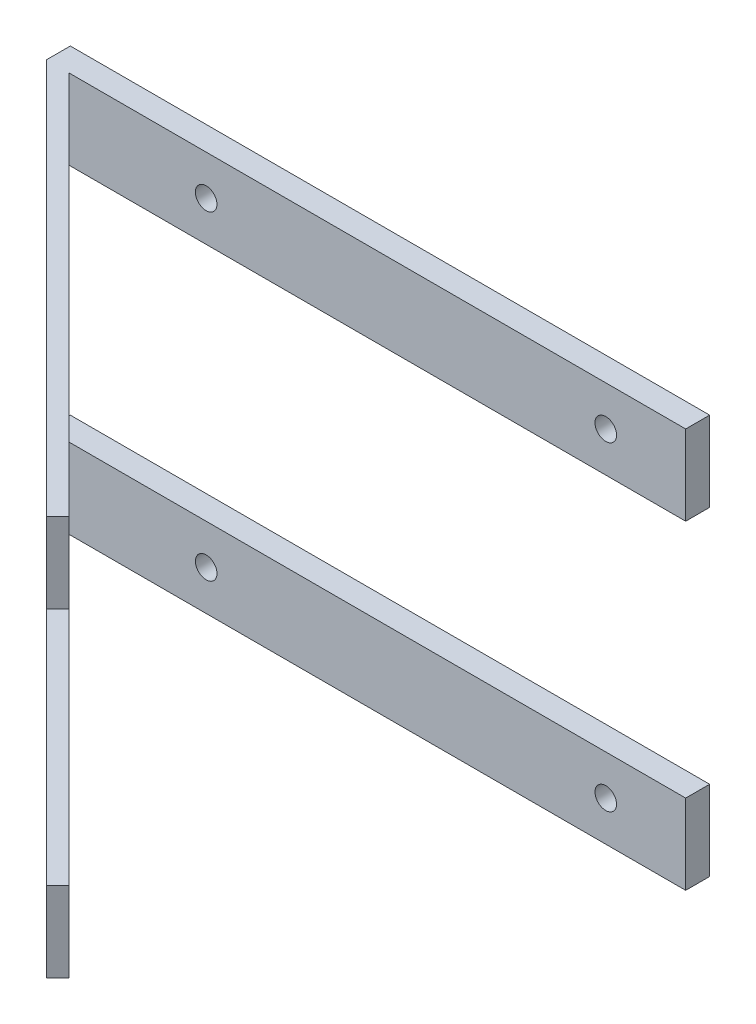
SolidWorks part; units mm, degrees
ref_plane "Alzado" through (0, 0, 0) normal (0, 0, 1) x (1, 0, 0)
ref_plane "Planta" through (0, 0, 0) normal (0, 1, 0) x (1, 0, 0)
ref_plane "Vista lateral" through (0, 0, 0) normal (1, 0, 0) x (0, 0, -1)
sketch "Croquis1" plane through (0, 0, 0) normal (0, 0, 1) x (1, 0, 0)
  line L0 (-50, 25) -> (40, 25) construction
  line L1 (-40, 10) -> (40, 10)
  line L2 (-40, 10) -> (-40, 0)
  line L3 (-40, 0) -> (40, 0)
  line L4 (40, 10) -> (40, 0)
  line L5 (40, 40) -> (40, 50)
  line L6 (-40, 50) -> (40, 50)
  line L7 (-40, 40) -> (-40, 50)
  line L8 (-40, 40) -> (40, 40)
  line L9 (-40, 5) -> (40, 5) construction
  line L10 (-40, 45) -> (40, 45) construction
  dimension "D1" = 10
  dimension "D2" = 15
  dimension "9" = 80
extrude "Saliente-Extruir1" add sketch "Croquis1" along normal blind 3 contours L7 L8 L5 L6 | L1 L4 L3 L2
sketch "Croquis2" plane through (0, 0, 0) normal (0, -1, 0) x (1, 0, 0)
  line L0 (-40, 3) -> (9.4975, 52.4975)
  line L1 (9.4975, 52.4975) -> (10.9117, 51.0833)
  line L2 (10.9117, 51.0833) -> (-37.1716, 3)
  line L3 (-40, 3) -> (40, 3) construction
  line L4 (-40, 3) -> (-37.1716, 3)
  dimension "D1" = 45
  dimension "D2" = 2
  dimension "D3" = 70
extrude "Saliente-Extruir2" add sketch "Croquis2" against normal up to surface (10 mm away) up to face at (0, 10, 1.5)
sketch "Croquis3" plane through (0, 50, 0) normal (0, 1, 0) x (1, 0, 0)
  line L0 (-40, -3) -> (9.4975, -52.4975)
  line L1 (9.4975, -52.4975) -> (10.9117, -51.0833)
  line L2 (10.9117, -51.0833) -> (-37.1716, -3)
  line L3 (-37.1716, -3) -> (-40, -3)
extrude "Saliente-Extruir3" add sketch "Croquis3" against normal up to surface (10 mm away) up to face at (0, 40, 1.5)
sketch "Croquis7" plane through (0, 0, 3) normal (0, 0, 1) x (1, 0, 0)
  line L0 (-40, 45) -> (40, 45) construction
  line L1 (-40, 40) -> (-40, 50) construction
  line L2 (40, 40) -> (40, 50) construction
  line L3 (-40, 5) -> (40, 5) construction
  line L4 (-40, 10) -> (-40, 0) construction
  line L5 (40, 10) -> (40, 0) construction
  line L6 (-20, 50) -> (-20, 0) construction
  line L7 (-40, 50) -> (9.4975, 50) construction
  line L8 (9.4975, 0) -> (-40, 0) construction
  line L9 (30, 50) -> (30, 0) construction
  line L10 (-37.1716, 50) -> (40, 50) construction
  line L11 (-37.1716, 0) -> (40, 0) construction
  dimension "D1" = 20
  dimension "D2" = 50
hole_wizard "Taladro de margen para M2.52" positions "Croquis3D3" profile "Croquis8" hole size "M2.5" standard "ISO" end condition through all
sketch3d "Croquis3D3"
  line L0 (-40, 45, 3) -> (40, 45, 3) construction
  line L1 (-20, 50, 3) -> (-20, 0, 3) construction
  line L2 (30, 50, 3) -> (30, 0, 3) construction
  line L3 (-40, 5, 3) -> (40, 5, 3) construction
  point P0 (-20, 45, 3)
  point P6 (30, 45, 3)
  point P10 (30, 5, 3)
  point P14 (-20, 5, 3)
sketch "Croquis8" plane through (-20, 45, 3) normal (1, 0, 0) x (0, -1, 0)
  line L0 (0, 0) -> (0, 3)
  line L1 (0, 3) -> (1.35, 3)
  line L2 (1.35, 3) -> (1.35, 0)
  line L5 (1.35, 0) -> (0, 0)
  line L11 (0, -6.35) -> (0, 107.95) construction
  dimension "Diámetro de taladro hasta el siguiente" = 2.7
  dimension "Profundidad de taladro hasta el siguiente" = 3
